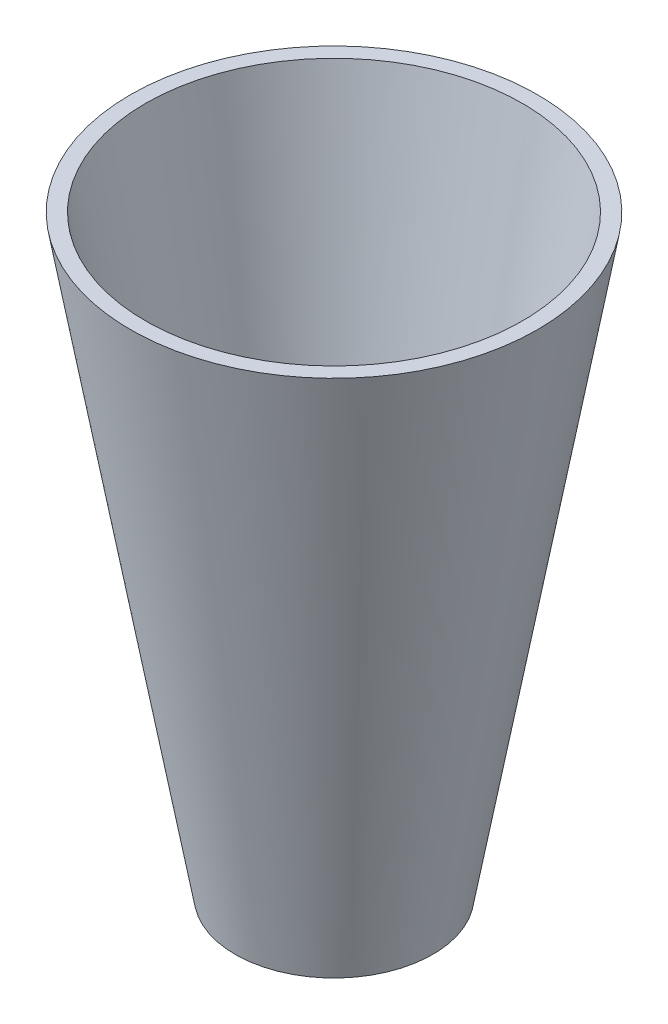
SolidWorks part; units mm, degrees
ref_plane "Front" through (0, 0, 0) normal (0, 0, 1) x (1, 0, 0)
ref_plane "Top" through (0, 0, 0) normal (0, 1, 0) x (1, 0, 0)
ref_plane "Right" through (0, 0, 0) normal (1, 0, 0) x (0, 0, -1)
sketch "Sketch1" plane through (0, 0, 0) normal (0, 0, 1) x (1, 0, 0)
  line L0 (0, 0) -> (10, 0)
  line L1 (10, 0) -> (20.5796, 60)
  line L2 (20.5796, 60) -> (19.0565, 60)
  line L3 (19.0565, 60) -> (8.7414, 1.5)
  line L4 (8.7414, 1.5) -> (0, 1.5)
  line L5 (0, 1.5) -> (0, 0)
  dimension "D1" = 1.5
  dimension "D2" = 1.5
  dimension "D3" = 10
  dimension "D4" = 100
  dimension "D5" = 60
revolve "Revolve1" add sketch "Sketch1" angle 360 about L5
